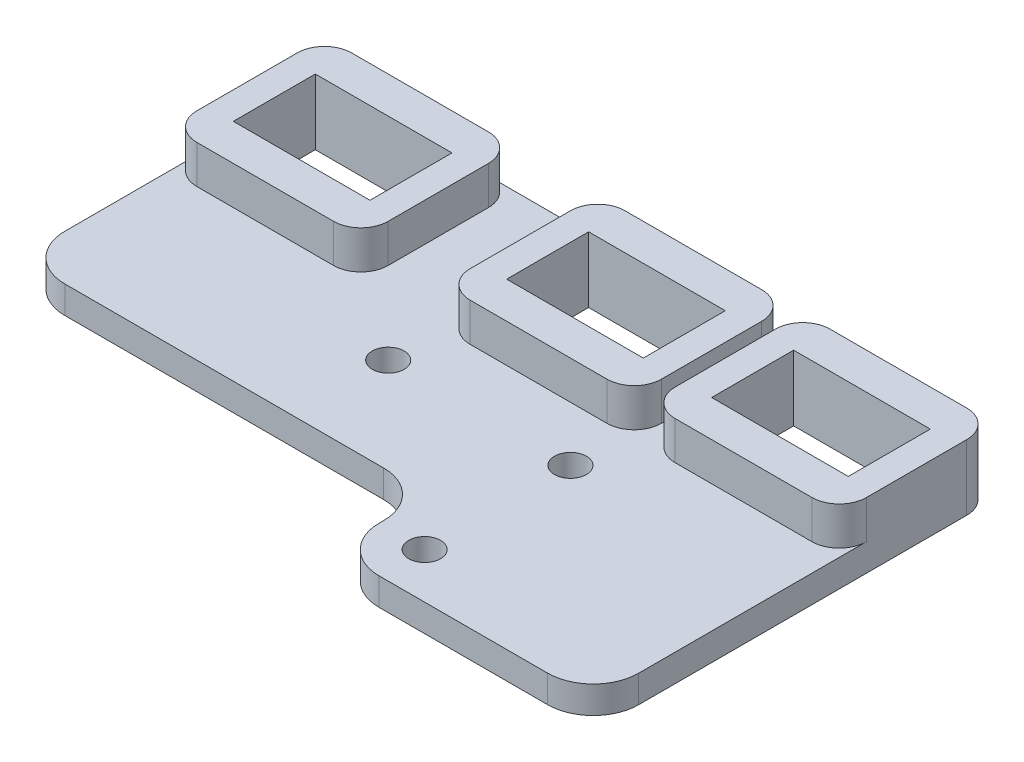
SolidWorks part; units mm, degrees
material "ABS"
ref_plane "前视基准面" through (0, 0, 0) normal (0, 0, 1) x (1, 0, 0)
ref_plane "上视基准面" through (0, 0, 0) normal (0, 1, 0) x (1, 0, 0)
ref_plane "右视基准面" through (0, 0, 0) normal (1, 0, 0) x (0, 0, -1)
other "Configuration Table"
sketch "草图1" plane through (0, 0, 0) normal (0, 1, 0) x (1, 0, 0)
  line L0 (0, 0) -> (0, -16) construction
  line L1 (0, 0) -> (-20, 0) construction
  line L2 (-20, 0) -> (-20, 21.5) construction
  line L3 (-20, 21.5) -> (-26, 21.5) construction
  line L4 (-26, 21.5) -> (-26, 0) construction
  line L5 (-26, 0) -> (-20, 0) construction
  line L6 (-20, 7.5) -> (23.5, 7.5) construction
  line L7 (23.5, 14.5) -> (-20, 14.5) construction
  line L8 (19.5, 7.5) -> (-16, 7.5) construction
  line L9 (23.5, 11.5) -> (23.5, 17.5) construction
  line L10 (19.5, 21.5) -> (-16, 21.5) construction
  line L11 (-20, 11.5) -> (-20, 17.5) construction
  line L12 (-17, 19) -> (-17, 10)
  line L13 (5.5, 19) -> (20.5, 19)
  line L14 (5.5, 19) -> (5.5, 10)
  line L15 (5.5, 10) -> (20.5, 10)
  line L16 (20.5, 19) -> (20.5, 10)
  line L17 (5.5, 19) -> (20.5, 10) construction
  line L18 (5.5, 10) -> (20.5, 19) construction
  line L19 (2.5, 6) -> (23.5, 6)
  line L20 (2.5, 6) -> (2.5, 23)
  line L21 (2.5, 23) -> (23.5, 23)
  line L22 (23.5, 6) -> (23.5, 23)
  line L23 (2.5, 6) -> (23.5, 23) construction
  line L24 (2.5, 23) -> (23.5, 6) construction
  line L25 (-17, 19) -> (-2, 19)
  line L26 (-2, 19) -> (-2, 10)
  line L27 (-17, 10) -> (-2, 10)
  line L28 (-20, 6) -> (-20, 23)
  line L29 (-20, 6) -> (1, 6)
  line L30 (1, 6) -> (1, 23)
  line L31 (-20, 23) -> (1, 23)
  line L32 (5.5, 19) -> (-17, 19) construction
  line L33 (-47, 19) -> (-47, 10)
  line L34 (-47, 19) -> (-32, 19)
  line L35 (-32, 19) -> (-32, 10)
  line L36 (-47, 10) -> (-32, 10)
  line L37 (-50, 6) -> (-50, 23)
  line L38 (-50, 6) -> (-29, 6)
  line L39 (-29, 6) -> (-29, 23)
  line L40 (-50, 23) -> (-29, 23)
  line L41 (5.5, 19) -> (-47, 19) construction
  circle A0 centre (0, 0) radius 1.75 construction
  circle A1 centre (0, -16) radius 1.75 construction
  circle A2 centre (-20, 0) radius 1.75 construction
  arc A3 (23.5, 11.5) -> (19.5, 7.5) centre (19.5, 11.5) cw construction
  arc A4 (23.5, 17.5) -> (19.5, 21.5) centre (19.5, 17.5) ccw construction
  arc A5 (-20, 11.5) -> (-16, 7.5) centre (-16, 11.5) ccw construction
  arc A6 (-16, 21.5) -> (-20, 17.5) centre (-16, 17.5) ccw construction
  point P26 (13, 14.5)
  point P31 (13, 14.5)
  dimension "D3" = 3.5
  dimension "D8" = 4
  dimension "D1" = 20
  dimension "D2" = 16
  dimension "D4" = 6
  dimension "D5" = 7.5
  dimension "D6" = 14
  dimension "D7" = 43.5
  dimension "D9" = 15
  dimension "D10" = 9
  dimension "D11" = 3
  dimension "D12" = 3
  dimension "D13" = 4
  dimension "D15" = 22.5
  dimension "D17" = 52.5
  dimension "D14" = 2
  dimension "D16" = 2
extrude "凸台-拉伸1" add sketch "草图1" along normal blind 4.2
sketch "草图2" plane through (0, 0, 0) normal (0, -1, 0) x (1, 0, 0)
  line L12 (-50, -23) -> (-50, 21)
  line L13 (-50, -23) -> (23.5, -23)
  line L14 (-50, 21) -> (23.5, 21)
  line L15 (23.5, -23) -> (23.5, 21)
  line L16 (-47, -19) -> (-32, -19) construction
  line L17 (-47, -19) -> (-47, -10) construction
  line L18 (-47, -10) -> (-32, -10) construction
  line L19 (-32, -19) -> (-32, -10) construction
  line L20 (-17, -19) -> (-2, -19) construction
  line L21 (-17, -19) -> (-17, -10) construction
  line L22 (-17, -10) -> (-2, -10) construction
  line L23 (-2, -19) -> (-2, -10) construction
  line L24 (5.5, -19) -> (20.5, -19) construction
  line L25 (20.5, -19) -> (20.5, -10) construction
  line L26 (5.5, -10) -> (20.5, -10) construction
  line L27 (5.5, -19) -> (5.5, -10) construction
  line L28 (-47, -19) -> (-32, -19)
  line L29 (-47, -19) -> (-47, -10)
  line L30 (-47, -10) -> (-32, -10)
  line L31 (-32, -19) -> (-32, -10)
  line L32 (-17, -19) -> (-2, -19)
  line L33 (-17, -19) -> (-17, -10)
  line L34 (-17, -10) -> (-2, -10)
  line L35 (-2, -19) -> (-2, -10)
  line L36 (5.5, -19) -> (20.5, -19)
  line L37 (20.5, -19) -> (20.5, -10)
  line L38 (5.5, -10) -> (20.5, -10)
  line L39 (5.5, -19) -> (5.5, -10)
  circle A0 centre (0, 0) radius 1.75 construction
  circle A1 centre (0, 16) radius 1.75 construction
  circle A2 centre (-20, 0) radius 1.75 construction
  circle A3 centre (0, 0) radius 1.75
  circle A4 centre (0, 16) radius 1.75
  circle A5 centre (-20, 0) radius 1.75
  dimension "D1" = 5
extrude "凸台-拉伸2" add sketch "草图2" along normal blind 3
fillet "圆角1" radius 3 12 edges at (-50, 2.1, -6) (-29, 2.1, -6) (-20, 2.1, -6) (2.5, 2.1, -6) (1, 2.1, -6) (2.5, 2.1, -23) (1, 2.1, -23) (-20, 2.1, -23) (-29, 2.1, -23) (23.5, 0.6, -23) (-50, 0.6, -23) (23.5, 2.1, -6)
sketch "草图3" plane through (0, 0, 0) normal (0, 1, 0) x (1, 0, 0)
  line L1 (-50, -21) -> (-5, -21)
  line L2 (-50, -21) -> (-50, -10.5)
  line L3 (-50, -10.5) -> (-5, -10.5)
  line L4 (-5, -21) -> (-5, -10.5)
  dimension "D1" = 45
  dimension "D2" = 10.5
extrude "切除-拉伸1" cut sketch "草图3" against normal through all
fillet "圆角2" radius 5 4 edges at (23.5, -1.5, 21) (-5, -1.5, 21) (-5, -1.5, 10.5) (-50, -1.5, 10.5)
